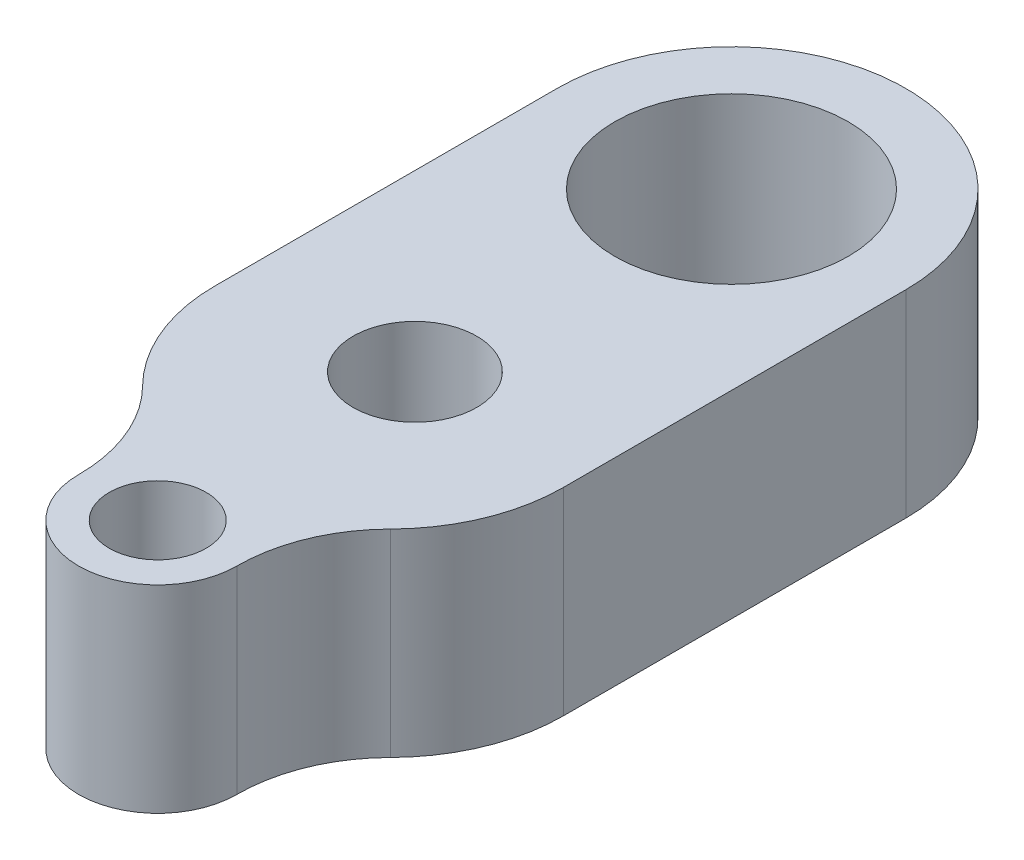
SolidWorks part; units mm, degrees
ref_plane "Front" through (0, 0, 0) normal (0, 0, 1) x (1, 0, 0)
ref_plane "Top" through (0, 0, 0) normal (0, 1, 0) x (1, 0, 0)
ref_plane "Right" through (0, 0, 0) normal (1, 0, 0) x (0, 0, -1)
sketch "Sketch1" plane through (0, 0, 0) normal (0, 1, 0) x (1, 0, 0)
  line L0 (-1.1389, -0.0804) -> (-1.1389, -2.2777)
  line L1 (-0.0198, -0.0804) -> (-0.0198, -4.4219) construction
  line L2 (-0.0198, -3.7634) -> (0.4882, -3.7634) construction
  line L3 (-0.0198, -4.0174) -> (-0.0198, -0.0804) construction
  line L4 (1.0994, -0.0804) -> (1.0994, -2.2777)
  line L5 (0.4882, -3.7634) -> (-0.5278, -3.7634) construction
  arc A0 (1.0994, -2.2777) -> (0.7755, -3.0652) centre (-0.0198, -2.2777) cw
  arc A1 (0.7755, -3.0652) -> (0.4882, -3.7634) centre (1.4804, -3.7634) ccw
  arc A2 (1.0994, -0.0804) -> (-1.1389, -0.0804) centre (-0.0198, -0.0804) ccw
  circle A3 centre (-0.0198, -3.7634) radius 0.3112
  circle A4 centre (-0.0198, -3.7634) radius 0.508
  arc A5 (-1.1389, -2.2777) -> (-0.815, -3.0652) centre (-0.0198, -2.2777) ccw
  circle A6 centre (-0.0198, -0.0804) radius 0.7493
  arc A7 (-0.815, -3.0652) -> (-0.5278, -3.7634) centre (-1.5199, -3.7634) cw
  circle A8 centre (-0.0198, -2.1124) radius 0.3969
  point P18 (-0.0198, -4.0174)
  dimension "D3" = 0.9922
  dimension "D4" = 0.6223
  dimension "D5" = 1.016
  dimension "D8" = 1.4986
  dimension "D9" = 0.7937
  dimension "D2" = 0.254
  dimension "D6" = 2.2384
  dimension "D7" = 2.032
  dimension "D10" = 1.651
  dimension "D1" = 180
extrude "Boss-Extrude1" add sketch "Sketch1" along normal blind 1.27 contours A5 A7 A4 A1 A0 L4 A2 L0 A8 A6 | A4 A3
sketch "Sketch3" plane through (0, 0, 0) normal (0, -1, 0) x (1, 0, 0)
  line L1 (-3.3064, 47.2846) -> (149.0936, 47.2846)
  line L2 (-3.3064, 47.2846) -> (-3.3064, -3.5154)
  line L3 (-3.3064, -3.5154) -> (149.0936, -3.5154)
  line L4 (149.0936, 47.2846) -> (149.0936, -3.5154)
  dimension "D1" = 50.8
  dimension "D2" = 152.4
